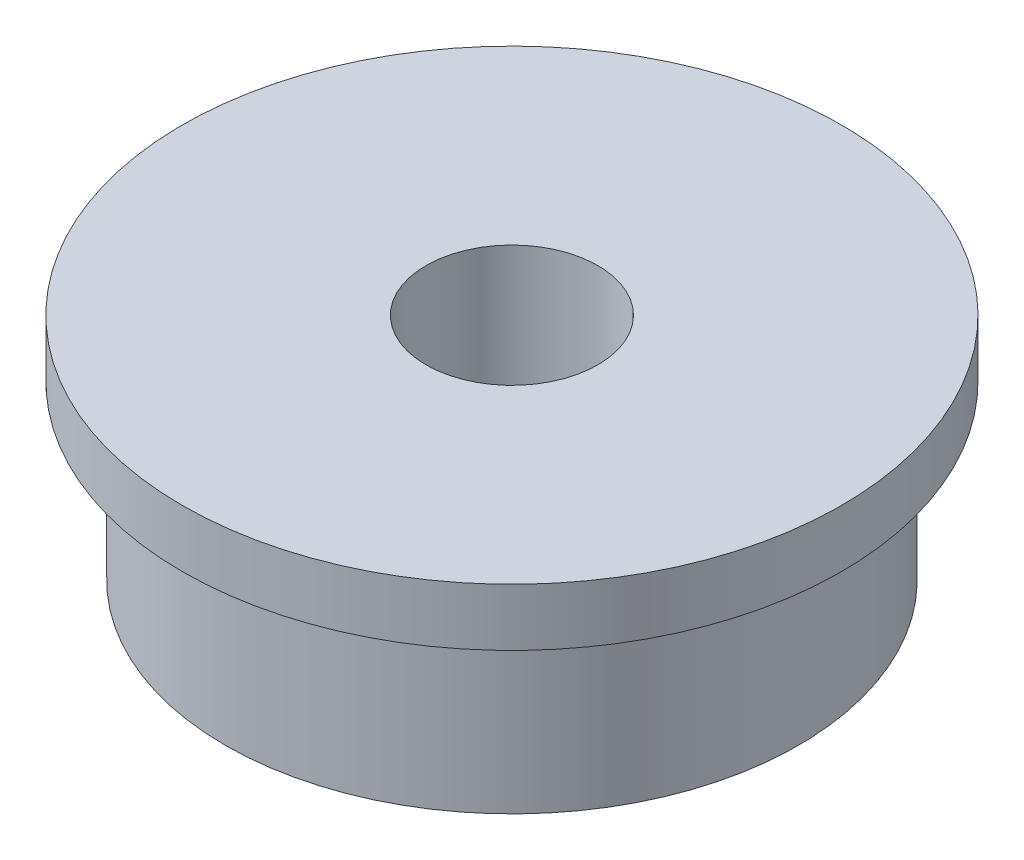
SolidWorks part; units mm, degrees
ref_plane "Front Plane" through (0, 0, 0) normal (0, 0, 1) x (1, 0, 0)
ref_plane "Top Plane" through (0, 0, 0) normal (0, 1, 0) x (1, 0, 0)
ref_plane "Right Plane" through (0, 0, 0) normal (1, 0, 0) x (0, 0, -1)
sketch "Sketch1" plane through (0, 0, 0) normal (0, 1, 0) x (1, 0, 0)
  circle A0 centre (0, 0) radius 1.5
  circle A1 centre (0, 0) radius 5
  dimension "D1" = 3
  dimension "D2" = 10
extrude "Boss-Extrude1" add sketch "Sketch1" along normal blind 4
sketch "Sketch2" plane through (0, 4, 0) normal (0, 1, 0) x (1, 0, 0)
  circle A0 centre (0, 0) radius 5 construction
  circle A1 centre (0, 0) radius 5
  circle A2 centre (0, 0) radius 5.75
  dimension "D1" = 11.5
extrude "Boss-Extrude2" add sketch "Sketch2" against normal blind 1
